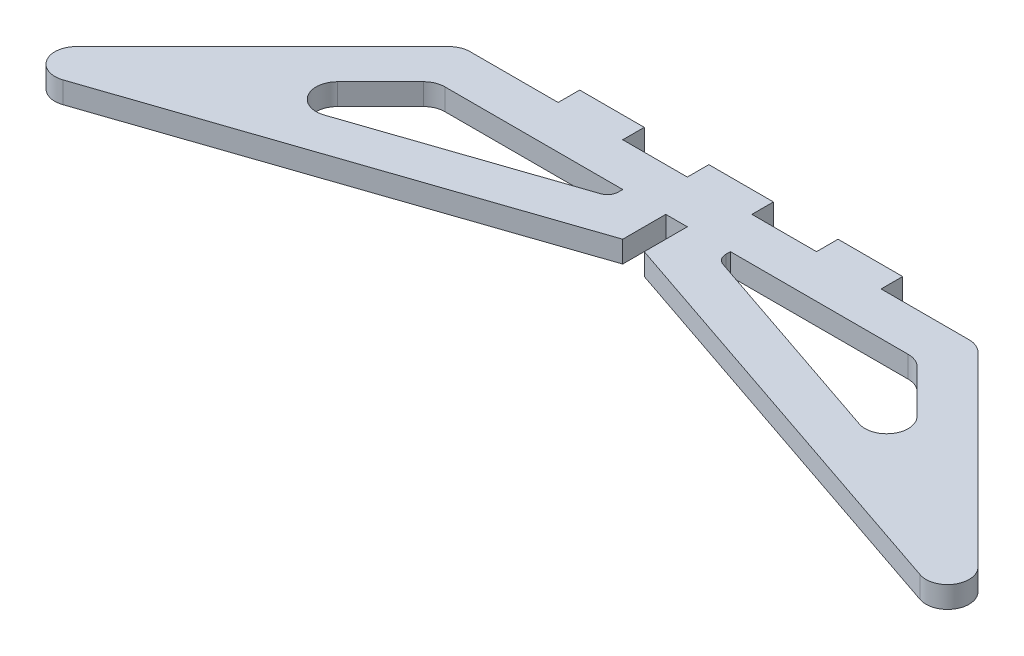
SolidWorks part; units mm, degrees
ref_plane "Front Plane" through (0, 0, 0) normal (0, 0, 1) x (1, 0, 0)
ref_plane "Top Plane" through (0, 0, 0) normal (0, 1, 0) x (1, 0, 0)
ref_plane "Right Plane" through (0, 0, 0) normal (1, 0, 0) x (0, 0, -1)
sketch "Sketch1" plane through (0, 0, 0) normal (0, 1, 0) x (1, 0, 0)
  line L0 (-36.7849, 0) -> (-23.8125, 0)
  line L1 (-1.5875, -6.35) -> (1.5875, -6.35)
  line L2 (4.7625, 3.175) -> (4.7625, 0)
  line L3 (-4.7625, 3.175) -> (-4.7625, 0)
  line L4 (14.2875, 3.175) -> (14.2875, 0)
  line L5 (23.8125, 3.175) -> (23.8125, 0)
  line L6 (-14.2875, 3.175) -> (-14.2875, 0)
  line L7 (-23.8125, 3.175) -> (-23.8125, 0)
  line L10 (-23.8125, 38.1) -> (-23.8125, -38.1) construction
  line L11 (-14.2875, 38.1) -> (-14.2875, -38.1) construction
  line L13 (-4.7625, 38.1) -> (-4.7625, -38.1) construction
  line L14 (-39.4529, -18.8505) -> (-9.0146, -8.5157)
  line L15 (4.7625, 38.1) -> (4.7625, -38.1) construction
  line L16 (14.2875, 38.1) -> (14.2875, -38.1) construction
  line L17 (23.8125, 38.1) -> (23.8125, -38.1) construction
  line L19 (-38.1, -6.35) -> (38.1, -6.35) construction
  line L20 (1.5875, -6.35) -> (1.5875, -12.7)
  line L21 (-1.5875, -6.35) -> (-1.5875, -12.7)
  line L22 (-14.2875, 0) -> (-4.7625, 0)
  line L23 (-38.1, 0) -> (38.1, 0) construction
  line L24 (4.7625, 0) -> (14.2875, 0)
  line L25 (-36.3997, -7.2799) -> (-42.7188, -13.599)
  line L26 (-34.1546, -6.35) -> (-7.9375, -6.35)
  line L27 (23.8125, 0) -> (36.7849, 0)
  line L28 (-39.0299, -0.9299) -> (-66.4691, -28.3691)
  line L29 (-63.2032, -33.6206) -> (-1.5875, -12.7)
  line L30 (39.4529, -18.8505) -> (9.0146, -8.5157)
  line L31 (63.2032, -33.6206) -> (1.5875, -12.7)
  line L32 (39.0299, -0.9299) -> (66.4691, -28.3691)
  line L33 (36.3997, -7.2799) -> (42.7188, -13.599)
  line L34 (7.9375, -6.35) -> (34.1546, -6.35)
  line L35 (-65.2448, -27.6077) -> (-3.6291, -6.6871) construction
  line L36 (-34.5398, -5.4201) -> (-61.9789, -32.8592) construction
  line L37 (-36.7849, -6.35) -> (-23.8125, -6.35) construction
  line L38 (23.8125, -6.35) -> (36.7849, -6.35) construction
  line L39 (34.5398, -5.4201) -> (61.9789, -32.8592) construction
  line L40 (65.2448, -27.6077) -> (3.6291, -6.6871) construction
  line L41 (-7.9375, -6.35) -> (-7.9375, -7.0125)
  line L42 (7.9375, -6.35) -> (7.9375, -7.0125)
  line L43 (-7.9375, -6.35) -> (-7.9375, -12.7) construction
  line L44 (7.9375, -6.35) -> (7.9375, -12.7) construction
  line L45 (-23.8125, 3.175) -> (-14.2875, 3.175)
  line L46 (-4.7625, 3.175) -> (4.7625, 3.175)
  line L47 (14.2875, 3.175) -> (23.8125, 3.175)
  arc A0 (-36.7849, 0) -> (-39.0299, -0.9299) centre (-36.7849, -3.175) ccw
  arc A1 (39.0299, -0.9299) -> (36.7849, 0) centre (36.7849, -3.175) ccw
  arc A2 (63.2032, -33.6206) -> (66.4691, -28.3691) centre (64.224, -30.6141) ccw
  arc A3 (-66.4691, -28.3691) -> (-63.2032, -33.6206) centre (-64.224, -30.6141) ccw
  arc A4 (39.4529, -18.8505) -> (42.7188, -13.599) centre (40.4737, -15.8441) ccw
  arc A5 (34.1546, -6.35) -> (36.3997, -7.2799) centre (34.1546, -9.525) cw
  arc A6 (-34.1546, -6.35) -> (-36.3997, -7.2799) centre (-34.1546, -9.525) ccw
  arc A7 (-39.4529, -18.8505) -> (-42.7188, -13.599) centre (-40.4737, -15.8441) cw
  arc A8 (9.0146, -8.5157) -> (7.9375, -7.0125) centre (9.525, -7.0125) cw
  arc A9 (-7.9375, -7.0125) -> (-9.0146, -8.5157) centre (-9.525, -7.0125) cw
extrude "Boss-Extrude1" add sketch "Sketch1" along normal blind 3.175
